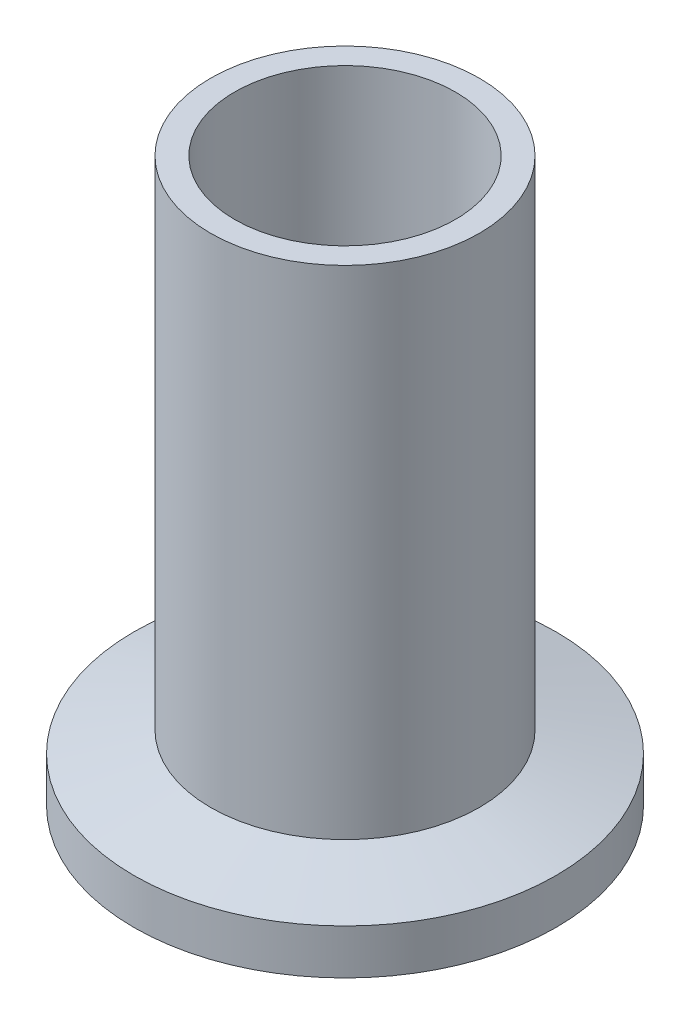
SolidWorks part; units mm, degrees
material "AISI 316 Annealed Stainless Steel Bar (SS)"
ref_plane "Front Plane" through (0, 0, 0) normal (0, 0, 1) x (1, 0, 0)
ref_plane "Top Plane" through (0, 0, 0) normal (0, 1, 0) x (1, 0, 0)
ref_plane "Right Plane" through (0, 0, 0) normal (1, 0, 0) x (0, 0, -1)
sketch "Sketch1" plane through (0, 0, 0) normal (1, 0, 0) x (0, 0, -1)
  line L0 (0, 0) -> (0, 5.4) construction
  line L1 (-15, 0) -> (-15, 3.2)
  line L2 (-15, 3.2) -> (-6.7895, 5.4)
  line L6 (0, 2.5) -> (-8.1, 2.5)
  line L7 (-8.1, 2.5) -> (-8.1, 0)
  line L8 (-8.1, 0) -> (-15, 0)
  line L9 (-6.7895, 5.4) -> (0, 5.4)
  line L10 (0, 5.4) -> (0, 2.5)
  dimension "D1" = 75
  dimension "D2" = 13.579
  dimension "Flange ID" = 16.2
  dimension "Flange OD" = 30
  dimension "D5" = 3.2
  dimension "Flange Height" = 5.4
  dimension "D9" = 2.5
revolve "Flange" add sketch "Sketch1" angle 360 about L0
sketch "Sketch5" plane through (0, 2.5, 0) normal (0, -1, 0) x (1, 0, 0)
  circle A0 centre (0, 0) radius 9.55
  dimension "Outer Diameter" = 19.1
extrude "Stub" add sketch "Sketch5" against normal offset from surface (37.5 mm away) 40 up to face at (0, 0, -8.1)
sketch "Bore Sketch" plane through (0, 40, 0) normal (0, 1, 0) x (1, 0, 0)
  circle A0 centre (0, 0) radius 7.85
  dimension "d1" = 15.7
ref_plane "Plane1" through (0, -1.905, 0) normal (0, -1, 0) x (-1, 0, 0)
extrude "Bore" cut sketch "Bore Sketch" against normal through all
